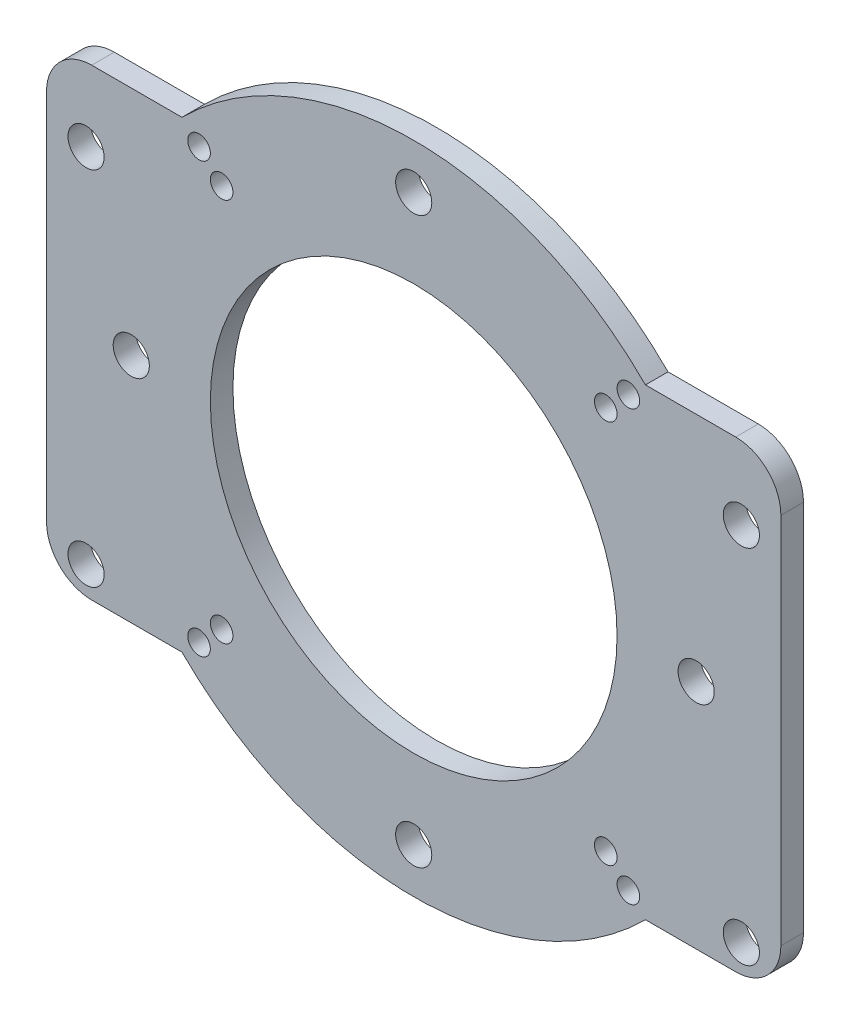
SolidWorks part; units mm, degrees
ref_plane "Front Plane" through (0, 0, 0) normal (0, 0, 1) x (1, 0, 0)
ref_plane "Top Plane" through (0, 0, 0) normal (0, 1, 0) x (1, 0, 0)
ref_plane "Right Plane" through (0, 0, 0) normal (1, 0, 0) x (0, 0, -1)
sketch "Sketch1" plane through (0, 0, 0) normal (0, 0, 1) x (1, 0, 0)
  line L0 (-32.5, 20.5) -> (-20.5122, 20.5)
  line L1 (32.5, 20.5) -> (32.5, -20.5)
  line L2 (32.5, -20.5) -> (20.5122, -20.5)
  line L3 (-32.5, -20.5) -> (-32.5, 20.5)
  line L4 (0, 39) -> (0, -40.7055) construction
  line L5 (-43.0364, 0) -> (51.1093, 0) construction
  line L6 (20.5122, 20.5) -> (32.5, 20.5)
  line L7 (-20.5122, -20.5) -> (-32.5, -20.5)
  arc A0 (-20.5122, -20.5) -> (20.5122, -20.5) centre (0, 0) ccw
  arc A1 (20.5122, 20.5) -> (-20.5122, 20.5) centre (0, 0) ccw
  circle A2 centre (0, 0) radius 18
  point P12 (26.5061, 20.5)
  dimension "D1" = 58
  dimension "D4" = 36
  dimension "D2" = 65
  dimension "D3" = 41
extrude "Boss-Extrude1" add sketch "Sketch1" along normal blind 2
sketch "Sketch2" plane through (0, 0, 2) normal (0, 0, 1) x (1, 0, 0)
  line L0 (-37.3479, -2) -> (38.9026, -2) construction
  line L1 (0, 32.4479) -> (0, -34.6372) construction
  line L2 (-7.3141, 0) -> (5.8301, 0) construction
  circle A0 centre (-29, 14) radius 1.6
  circle A1 centre (-29, -18) radius 1.6
  circle A2 centre (29, -18) radius 1.6
  circle A3 centre (29, 14) radius 1.6
  point P15 (0, 0)
  point P16 (0, 0)
  dimension "D1" = 3.2
  dimension "D2" = 58
  dimension "D3" = 32
  dimension "D4" = 2
extrude "Cut-Extrude1" cut sketch "Sketch2" against normal blind 2
sketch "Sketch3" plane through (0, 0, 2) normal (0, 0, 1) x (1, 0, 0)
  line L0 (0, 15.6309) -> (0, -13.6849) construction
  line L1 (-12.5553, 0) -> (11.836, 0) construction
  point P5 (-17, 17)
  point P6 (17, 17)
  point P7 (17, -17)
  point P8 (-17, -17)
  point P9 (19, 19)
  point P10 (19, -19)
  point P11 (-19, -19)
  point P13 (-19, 19)
  dimension "D1" = 34
  dimension "D2" = 34
  dimension "D3" = 38
  dimension "D4" = 38
hole_wizard "Ø2.0mm Dowel Hole1" positions "3DSketch1" profile "Sketch4" hole size "Ø2.0" standard "ANSI Metric" end condition through all
sketch3d "3DSketch1"
  point P0 (-19, 19, 2)
  point P3 (-17, 17, 2)
  point P6 (17, 17, 2)
  point P9 (19, 19, 2)
  point P12 (17, -17, 2)
  point P15 (19, -19, 2)
  point P18 (-19, -19, 2)
  point P21 (-17, -17, 2)
sketch "Sketch4" plane through (-19, 19, 2) normal (1, 0, 0) x (0, -1, 0)
  line L0 (0, 0) -> (0, 2)
  line L1 (0, 2) -> (1, 2)
  line L2 (1, 2) -> (1, 0)
  line L5 (1, 0) -> (0, 0)
  line L11 (0, -6.35) -> (0, 107.95) construction
  dimension "Thru Hole Dia." = 2
  dimension "Thru Hole Depth" = 2
sketch "Sketch5" plane through (0, 0, 0) normal (0, 0, 1) x (1, 0, 0)
  line L2 (0, 0) -> (14.1533, 0) construction
  line L3 (0, 0) -> (0, 14.1167) construction
  line L4 (0, 15.6309) -> (0, -13.6849) construction
  circle A0 centre (0, 25) radius 1.6
  circle A1 centre (-25, 0) radius 1.6
  circle A2 centre (25, 0) radius 1.6
  circle A3 centre (0, -25) radius 1.6
  dimension "D1" = 3.2
  dimension "D2" = 50
  dimension "D3" = 50
extrude "Cut-Extrude4" cut sketch "Sketch5" along normal through all
fillet "Fillet1" radius 4 4 edges at (-32.5, -20.5, 1) (-32.5, 20.5, 1) (32.5, 20.5, 1) (32.5, -20.5, 1)
